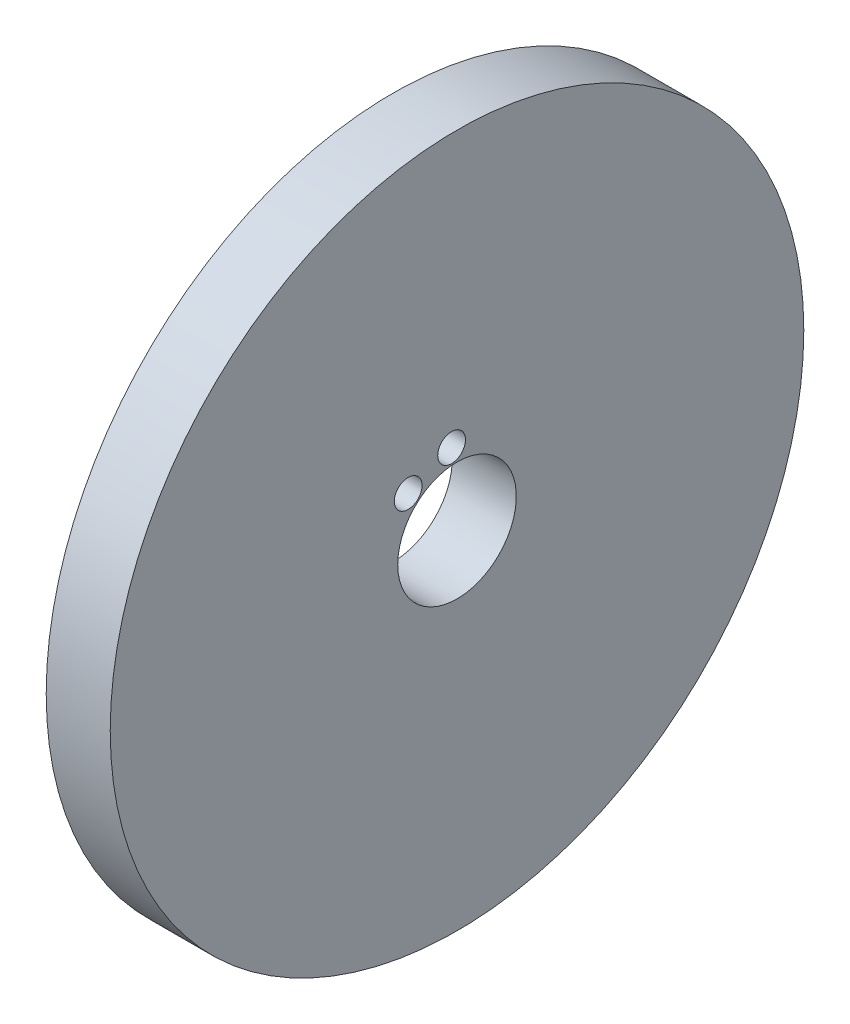
SolidWorks part; units mm, degrees
ref_plane "Front Plane" through (0, 0, 0) normal (0, 0, 1) x (1, 0, 0)
ref_plane "Top Plane" through (0, 0, 0) normal (0, 1, 0) x (1, 0, 0)
ref_plane "Right Plane" through (0, 0, 0) normal (1, 0, 0) x (0, 0, -1)
sketch "Axial profile (mm)" plane through (0, 0, 0) normal (0, 0, 1) x (1, 0, 0)
  line L0 (-110, 0) -> (75, 0) construction
  line L1 (13.7, 11.1125) -> (25.7, 11.1125)
  line L2 (25.7, 11.1125) -> (25.7, 65)
  line L3 (25.7, 65) -> (13.7, 65)
  line L4 (13.7, 65) -> (13.7, 11.1125)
revolve "Full revolution" add sketch "Axial profile (mm)" angle 360 about L0
sketch "Sketch2" plane through (0, 0, 0) normal (1, 0, 0) x (0, 0, -1)
  circle A0 centre (-1.0169, 13.963) radius 2.6
  circle A1 centre (-9.1543, 10.5924) radius 2.6
extrude "Axial holes" cut sketch "Sketch2" against normal through all and the other way through all
